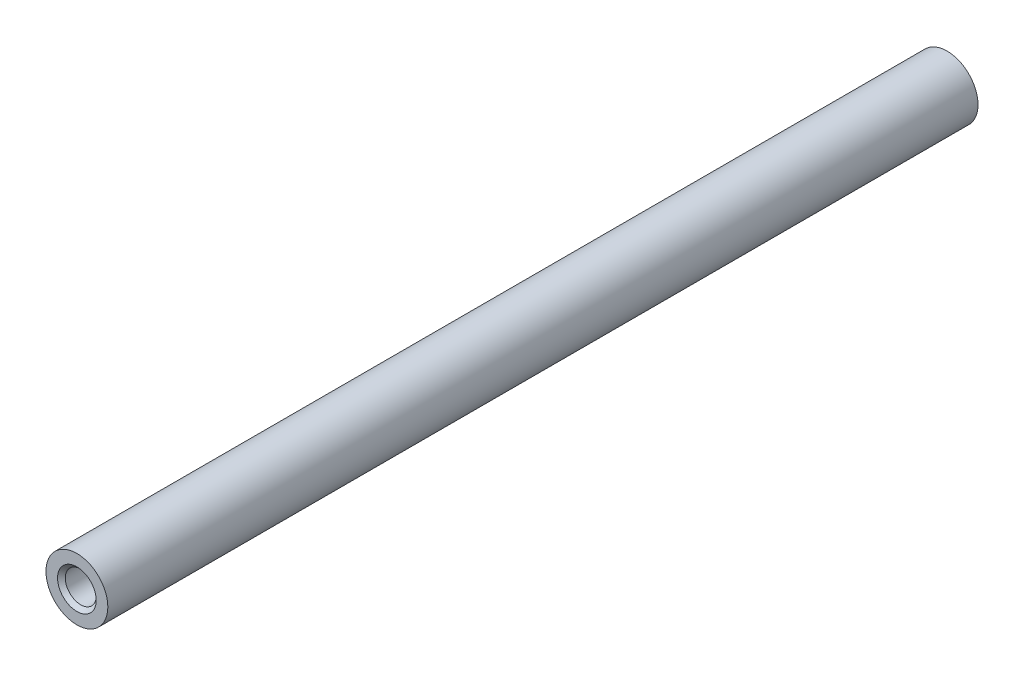
SolidWorks part; units mm, degrees
material "1.0545 (S355N)"
ref_plane "Płaszczyzna przednia" through (0, 0, 0) normal (0, 0, 1) x (1, 0, 0)
ref_plane "Płaszczyzna górna" through (0, 0, 0) normal (0, 1, 0) x (1, 0, 0)
ref_plane "Płaszczyzna prawa" through (0, 0, 0) normal (1, 0, 0) x (0, 0, -1)
sketch "Szkic1" plane through (0, 0, 0) normal (0, 0, 1) x (1, 0, 0)
  circle A0 centre (0, 0) radius 8
  circle A1 centre (0, 0) radius 4
  dimension "D1" = 4
  dimension "D2" = 16
extrude "Dodanie-wyciągnięcie1" add sketch "Szkic1" along normal mid plane 225
sketch "Szkic2" plane through (0, 0, -112.5) normal (0, 0, -1) x (-1, 0, 0)
  circle A0 centre (0, 0) radius 5
  circle A1 centre (0, 0) radius 4 construction
  dimension "D1" = 1
extrude "Wytnij-wyciągnięcie1" cut sketch "Szkic2" against normal blind 30
chamfer "Sfazowanie1" distance 1 angle 45 1 edges at (4, 0, 112.5)
